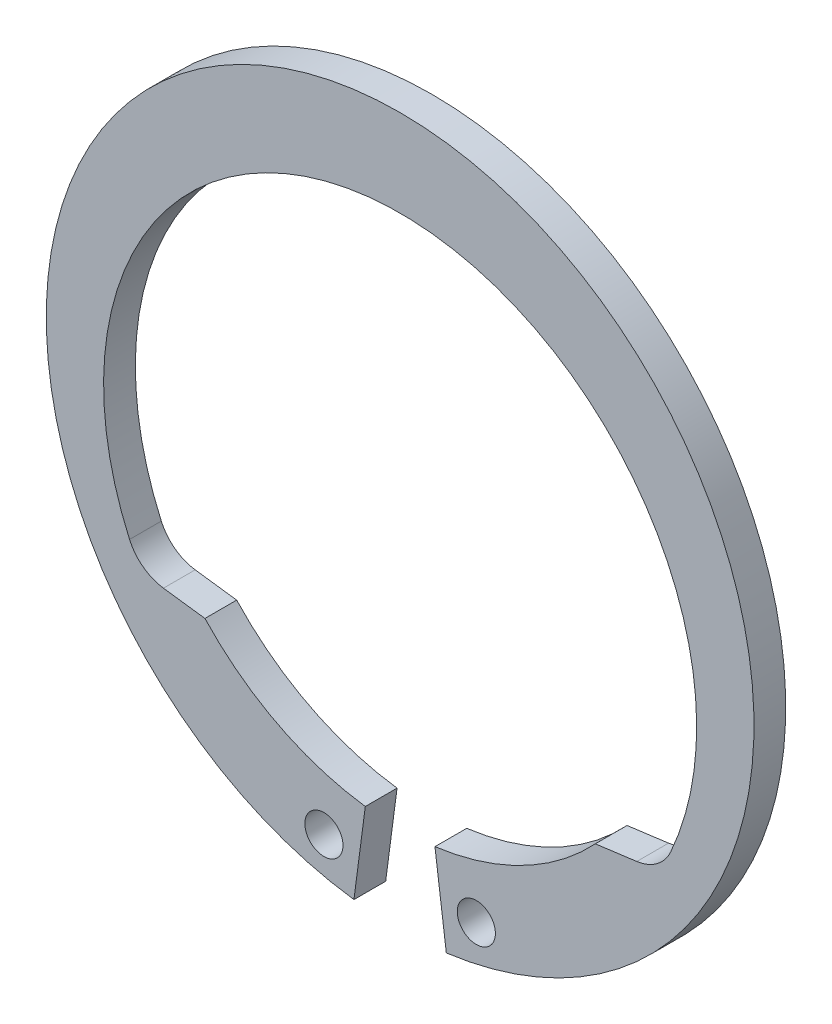
SolidWorks part; units mm, degrees
ref_plane "Plane1" through (0, 0, 0) normal (0, 0, 1) x (1, 0, 0)
ref_plane "Plane2" through (0, 0, 0) normal (0, 1, 0) x (1, 0, 0)
ref_plane "Plane3" through (0, 0, 0) normal (1, 0, 0) x (0, 0, -1)
sketch "Clipboard" plane through (0, 0, 0) normal (0, 0, 1) x (1, 0, 0)
  line L0 (0, 0) -> (1.7272, 0)
  line L1 (0, 0) -> (0, 1.2192)
  line L2 (0, 0) -> (0, -2.4384)
  circle A0 centre (0, 0) radius 0.5334
  circle A1 centre (0, 0) radius 7.9375
  dimension "HoleDia" = 1.0668
  dimension "ShaftDia" = 15.875
  dimension "SmallSection" = 1.2192
  dimension "LugSection" = 2.4384
sketch "BodySke" plane through (0, 0, 0) normal (0, 0, 1) x (1, 0, 0)
  line L0 (0, 0) -> (0, 11.176) construction
  line L1 (-0.9747, -7.4037) -> (-1.293, -9.8213)
  line L2 (0.9747, -7.4037) -> (1.293, -9.8213)
  line L3 (0, 0) -> (-7.523, -4.3434) construction
  line L4 (0, 0) -> (7.523, -4.3434) construction
  line L5 (6.6256, -4.9372) -> (5.464, -5.0901)
  line L6 (-6.6256, -4.9372) -> (-5.464, -5.0901)
  line L7 (1.942, -7.2107) -> (2.2624, -9.6442) construction
  line L8 (-1.942, -7.2107) -> (-2.2624, -9.6442) construction
  arc A0 (0.9747, -7.4037) -> (5.464, -5.0901) centre (0, 0) ccw
  arc A1 (7.5747, -4.2304) -> (-7.5747, -4.2304) centre (0, -0.8338) ccw
  arc A2 (-5.464, -5.0901) -> (-0.9747, -7.4037) centre (0, 0) ccw
  arc A3 (6.6256, -4.9372) -> (7.5747, -4.2304) centre (6.4671, -3.7338) ccw
  arc A4 (-7.5747, -4.2304) -> (-6.6256, -4.9372) centre (-6.4671, -3.7338) ccw
  arc A5 (0.9747, -7.4037) -> (-0.9747, -7.4037) centre (0, 0) ccw construction
  arc A6 (7.523, -4.3434) -> (-7.523, -4.3434) centre (0, -0.8338) ccw construction
  arc A7 (1.1645, -8.8454) -> (-1.1645, -8.8454) centre (0, 0) ccw construction
  arc A8 (1.293, -9.8213) -> (-1.293, -9.8213) centre (0, 0) ccw
  circle A9 centre (2.1332, -8.663) radius 0.5334
  circle A10 centre (-2.1332, -8.663) radius 0.5334
  dimension "GrooveDia" = 14.9352
  dimension "OutsideDia" = 19.812
  dimension "HoleOffsetRad" = 8.9217
  dimension "HoleDia" = 1.0668
  dimension "GapAngle" = 15
  dimension "D1" = 120
  dimension "SmallRad" = 8.6868
  dimension "HoleOffset" = 0.9843
extrude "Body" add sketch "BodySke" against normal blind 0.889
equation "' \"ShaftDia@Clipboard\" = 0.5"
equation "' \"Thickness@Body\" = 0.035"
equation "' \"GrooveDia@BodySke\" = 0.468"
equation "' \"LugSection@Clipboard\" = 0.08"
equation "' \"SmallSection@Clipboard\" = 0.041"
equation "' \"HoleDia@Clipboard\" = 0.042"
equation "' \"ShaftDia@Clipboard\" = 0.625"
equation "' \"GrooveDia@BodySke\" = 0.588"
equation "' \"LugSection@Clipboard\" = 0.096"
equation "' \"SmallSection@Clipboard\" = 0.048"
equation "\"OutsideDia@BodySke\" = \"GrooveDia@BodySke\" + \"LugSection@Clipboard\" * 2"
equation "\"SmallRad@BodySke\" =  \"GrooveDia@BodySke\" / 2 +  \"SmallSection@Clipboard\""
equation "\"HoleOffsetRad@BodySke\" = ( \"OutsideDia@BodySke\" + \"ShaftDia@Clipboard\" ) / 4"
equation "\"HoleOffset@BodySke\" = \"OutsideDia@BodySke\" / 2 - \"HoleOffsetRad@BodySke\" "
equation "\"HoleDia@BodySke\" = \"HoleDia@Clipboard\""
